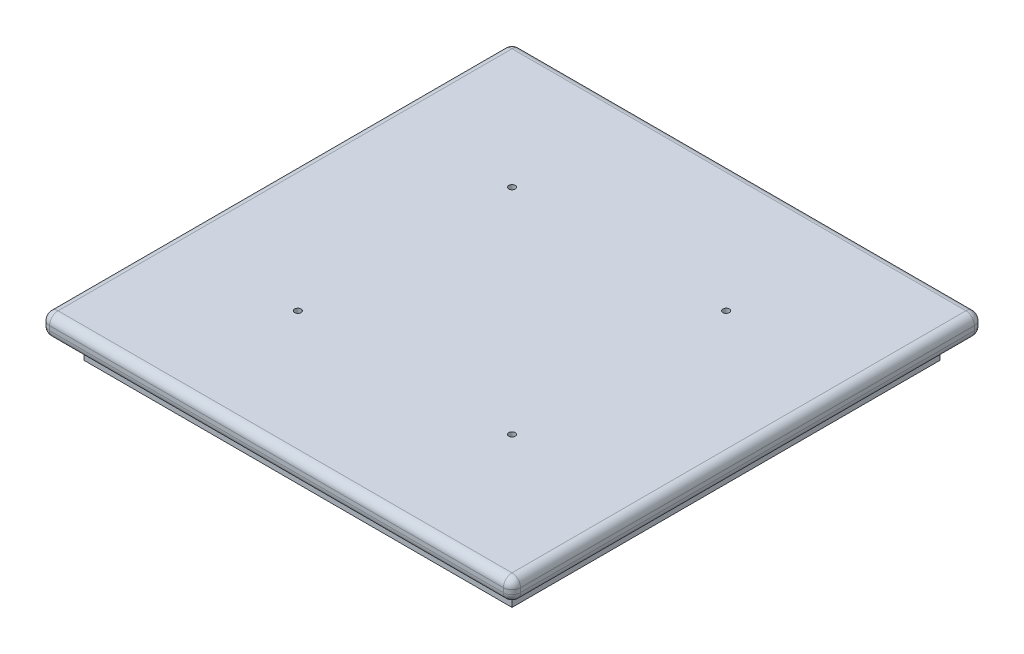
SolidWorks part; units mm, degrees
ref_plane "Front Plane" through (0, 0, 0) normal (0, 0, 1) x (1, 0, 0)
ref_plane "Top Plane" through (0, 0, 0) normal (0, 1, 0) x (1, 0, 0)
ref_plane "Right Plane" through (0, 0, 0) normal (1, 0, 0) x (0, 0, -1)
sketch "Sketch1" plane through (0, 0, 0) normal (0, 1, 0) x (1, 0, 0)
  line L0 (-50, 0) -> (50, 0) construction
  line L1 (50, 50) -> (-50, 50)
  line L2 (50, 50) -> (50, -50)
  line L3 (50, -50) -> (-50, -50)
  line L4 (-50, 50) -> (-50, -50)
  line L5 (50, 50) -> (-50, -50) construction
  line L6 (50, -50) -> (-50, 50) construction
  circle A0 centre (-25, 25) radius 0.75
  circle A1 centre (25, -25) radius 0.75
  circle A2 centre (25, 25) radius 0.75
  circle A3 centre (-25, -25) radius 0.75
  point P0 (0, 0)
  dimension "D4" = 1.5
  dimension "D1" = 100
  dimension "D2" = 100
  dimension "D3" = 25
extrude "Boss-Extrude1" add sketch "Sketch1" along normal blind 10
sketch "Sketch2" plane through (0, 10, 0) normal (0, 1, 0) x (1, 0, 0)
  line L11 (50, 50) -> (-50, 50)
  line L12 (50, 50) -> (50, -50)
  line L13 (50, -50) -> (-50, -50)
  line L14 (-55, 55) -> (-55, -55)
  line L15 (-55, -55) -> (55, -55)
  line L16 (55, -55) -> (55, 55)
  line L17 (55, 55) -> (-55, 55)
  line L18 (-55, 55) -> (-55, -55)
  line L19 (-55, -55) -> (55, -55)
  line L20 (55, -55) -> (55, 55)
  line L21 (55, 55) -> (-55, 55)
  line L22 (-50, 50) -> (-50, -50)
  line L23 (50, 50) -> (-50, -50) construction
  line L24 (50, -50) -> (-50, 50) construction
  point P0 (0, 0)
  dimension "D1" = 5
extrude "Boss-Extrude3" add sketch "Sketch2" against normal blind 5
fillet "Fillet2" radius 2 12 edges at (-55, 5, 0) (-55, 10, 0) (0, 5, 55) (-55, 7.5, 55) (0, 10, 55) (55, 5, 0) (55, 7.5, 55) (55, 10, 0) (-55, 7.5, -55) (0, 5, -55) (55, 7.5, -55) (0, 10, -55)
